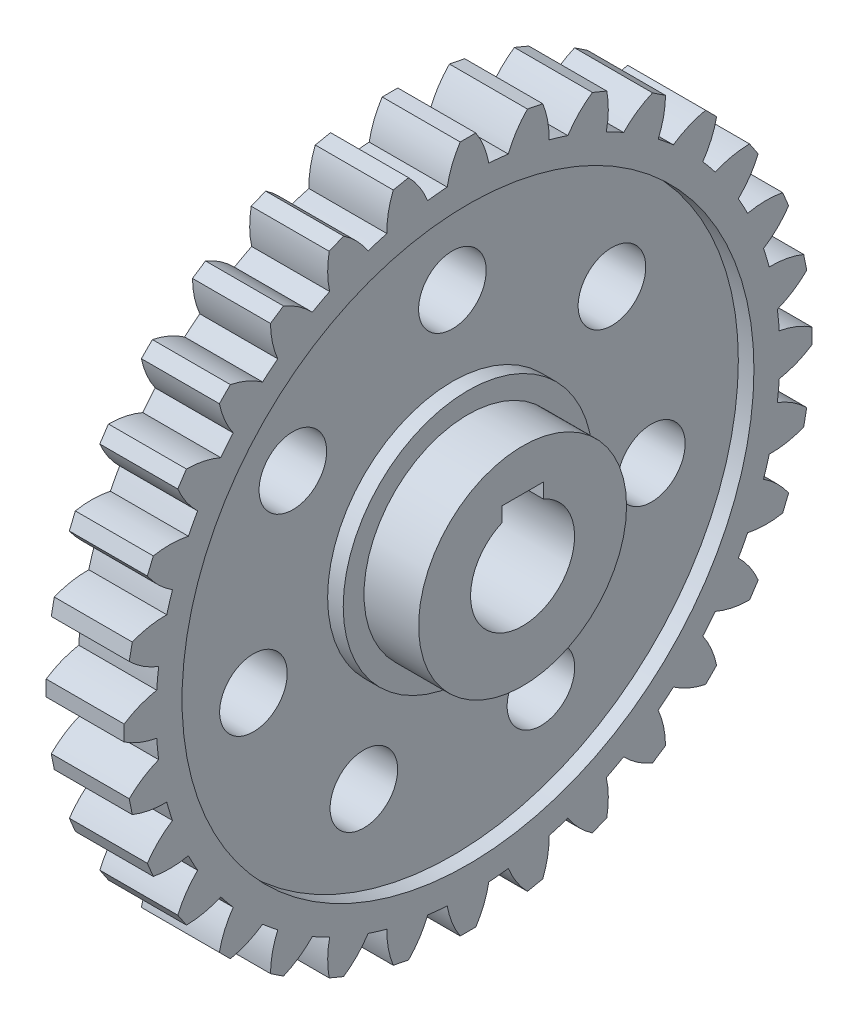
SolidWorks part; units mm, degrees
ref_plane "Front Plane" through (0, 0, 0) normal (0, 0, 1) x (1, 0, 0)
ref_plane "Top Plane" through (0, 0, 0) normal (0, 1, 0) x (1, 0, 0)
ref_plane "Right Plane" through (0, 0, 0) normal (1, 0, 0) x (0, 0, -1)
sketch "Sketch1" plane through (0, 0, 0) normal (1, 0, 0) x (0, 0, -1)
  circle A0 centre (0, 0) radius 60
  dimension "D1" = 120
extrude "Boss-Extrude1" add sketch "Sketch1" along normal mid plane 15
sketch "Sketch2" plane through (7.5, 0, 0) normal (1, 0, 0) x (0, 0, -1)
  line L0 (0, 0) -> (1.6044, 0) construction
  line L1 (0, 0) -> (0, 83.3894) construction
  line L2 (-1.5, 66.1335) -> (1.5, 66.1335)
  arc A0 (-4, 59.8665) -> (4, 59.8665) centre (0, 0) cw
  circle A1 centre (0, 0) radius 60 construction
  arc A2 (-4, 59.8665) -> (-1.5, 66.1335) centre (12.726, 56.8264) cw
  arc A3 (4, 59.8665) -> (1.5, 66.1335) centre (-12.726, 56.8264) ccw
  point P12 (0, 66.1335)
  dimension "D4" = 17
  dimension "D1" = 3
  dimension "D2" = 6.267
  dimension "D3" = 4
extrude "Boss-Extrude2" add sketch "Sketch2" against normal up to surface (15 mm away) up to face at (-7.5, 0, -60)
pattern_circular "CirPattern1" count 32 over 360 about axis through (0, 0, 0) along (1, 0, 0) of "Boss-Extrude2"
sketch "Sketch3" plane through (0, 0, 0) normal (1, 0, 0) x (0, 0, -1)
  circle A0 centre (0, 0) radius 20
  dimension "D1" = 40
extrude "Boss-Extrude4" add sketch "Sketch3" along normal mid plane 36
sketch "Sketch5" plane through (18, 0, 0) normal (1, 0, 0) x (0, 0, -1)
  line L0 (0, 0) -> (0, 12) construction
  line L1 (-4, 12) -> (4, 12)
  line L2 (-4, 12) -> (-4, 9.1652)
  line L3 (4, 12) -> (4, 9.1652)
  arc A0 (-4, 9.1652) -> (4, 9.1652) centre (0, 0) ccw
  point P7 (0, 12)
  dimension "D1" = 20
  dimension "D2" = 12
  dimension "D3" = 8
extrude "Cut-Extrude1" cut sketch "Sketch5" against normal through all
sketch "Sketch6" plane through (7.5, 0, 0) normal (1, 0, 0) x (0, 0, -1)
  circle A0 centre (0, 0) radius 55
  circle A1 centre (0, 0) radius 24
  dimension "D1" = 110
  dimension "D2" = 48
extrude "Cut-Extrude2" cut sketch "Sketch6" against normal blind 3
sketch "Sketch7" plane through (4.5, 0, 0) normal (1, 0, 0) x (0, 0, -1)
  circle A0 centre (0, 0) radius 39.25 construction
  circle A1 centre (0, 39.25) radius 6.5
  circle A2 centre (0, 0) radius 39.25 construction
  circle A3 centre (30.6869, 24.472) radius 6.5
  circle A4 centre (0, 0) radius 39.25 construction
  circle A5 centre (38.2659, -8.7339) radius 6.5
  circle A6 centre (0, 0) radius 39.25 construction
  circle A7 centre (17.0299, -35.363) radius 6.5
  circle A8 centre (0, 0) radius 39.25 construction
  circle A9 centre (-17.0299, -35.363) radius 6.5
  circle A10 centre (0, 0) radius 39.25 construction
  circle A11 centre (-38.2659, -8.7339) radius 6.5
  circle A12 centre (0, 0) radius 39.25 construction
  circle A13 centre (-30.6869, 24.472) radius 6.5
  point P26 (0, 0)
  dimension "D1" = 78.5
  dimension "D2" = 13
  dimension "D3" = 7
extrude "Cut-Extrude3" cut sketch "Sketch7" against normal through all
